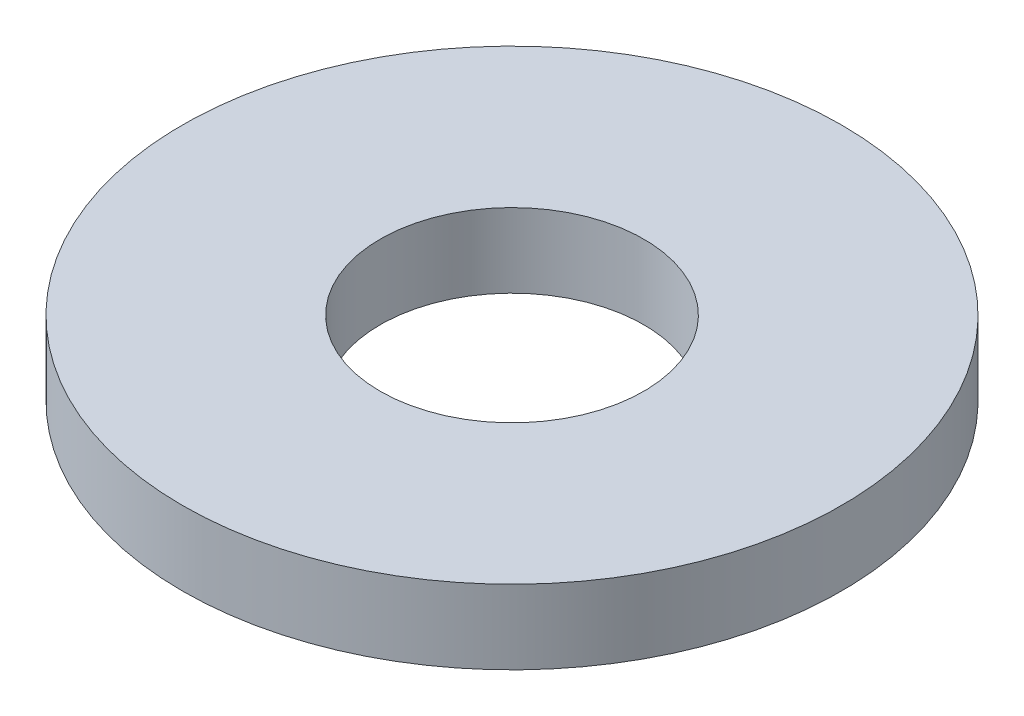
SolidWorks part; units mm, degrees
ref_plane "Front Plane" through (0, 0, 0) normal (0, 0, 1) x (1, 0, 0)
ref_plane "Top Plane" through (0, 0, 0) normal (0, 1, 0) x (1, 0, 0)
ref_plane "Right Plane" through (0, 0, 0) normal (1, 0, 0) x (0, 0, -1)
sketch "Sketch1" plane through (0, 0, 0) normal (0, 1, 0) x (1, 0, 0)
  circle A0 centre (0, 0) radius 4
  dimension "OD" = 8
extrude "Boss-Extrude1" add sketch "Sketch1" along normal blind 0.9
sketch "Sketch5" plane through (0, 0.9, 0) normal (0, 1, 0) x (-1, 0, 0)
  circle A0 centre (0, 0) radius 1.6
  dimension "ID" = 3.2
extrude "Cut-Extrude1" cut sketch "Sketch5" against normal through all
